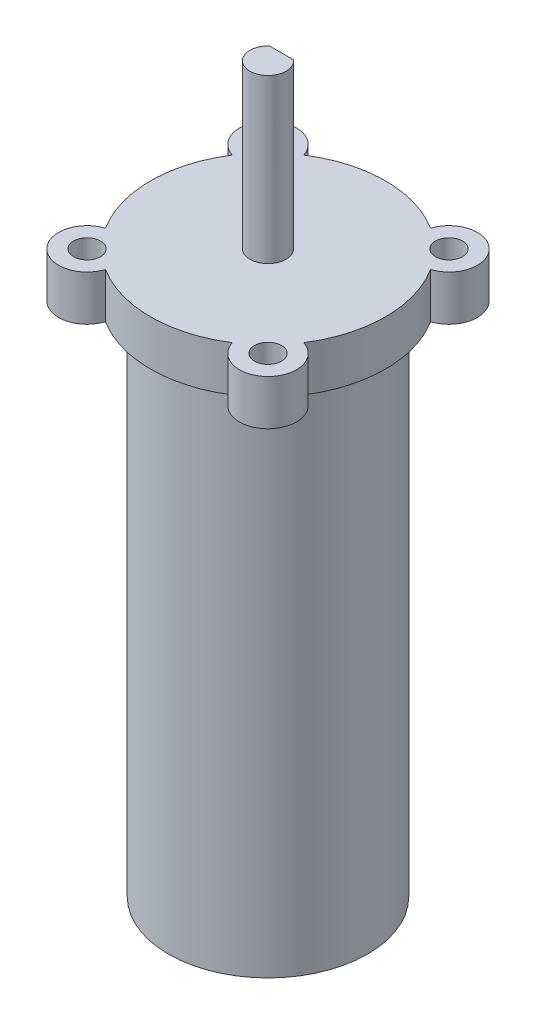
SolidWorks part; units mm, degrees
ref_plane "前视基准面" through (0, 0, 0) normal (0, 0, 1) x (1, 0, 0)
ref_plane "上视基准面" through (0, 0, 0) normal (0, 1, 0) x (1, 0, 0)
ref_plane "右视基准面" through (0, 0, 0) normal (1, 0, 0) x (0, 0, -1)
sketch "Sketch1" plane through (0, 0, 0) normal (0, 1, 0) x (1, 0, 0)
  circle A0 centre (0, 0) radius 11
extrude "Extrude1" add sketch "Sketch1" along normal blind 62
sketch "Sketch2" plane through (0, 62, 0) normal (0, 1, 0) x (1, 0, 0)
  circle A0 centre (0, 0) radius 2
extrude "Extrude2" add sketch "Sketch2" along normal blind 18
sketch "Sketch3" plane through (0, 0, 0) normal (0, -1, 0) x (1, 0, 0)
  circle A0 centre (10, -10) radius 1.5
  circle A1 centre (10, 10) radius 1.5
  circle A2 centre (-10, 10) radius 1.5
  circle A3 centre (-10, -10) radius 1.5
  circle A4 centre (0, 0) radius 11 construction
  circle A5 centre (0, 0) radius 11
  arc A6 (10.9511, -7.0053) -> (10.9511, 7.0053) centre (0, 0) ccw
  arc A7 (7.0053, -10.9511) -> (10.9511, -7.0053) centre (10, -10) ccw
  arc A8 (10.9511, 7.0053) -> (7.0053, 10.9511) centre (10, 10) ccw
  arc A9 (-7.0053, 10.9511) -> (-10.9511, 7.0053) centre (-10, 10) ccw
  arc A10 (-10.9511, -7.0053) -> (-7.0053, -10.9511) centre (-10, -10) ccw
  circle A11 centre (0, 0) radius 13 construction
  arc A12 (7.0053, 10.9511) -> (-7.0053, 10.9511) centre (0, 0) ccw
  arc A13 (-10.9511, 7.0053) -> (-10.9511, -7.0053) centre (0, 0) ccw
  arc A14 (-7.0053, -10.9511) -> (7.0053, -10.9511) centre (0, 0) ccw
  dimension "D1" = 2
extrude "Extrude3" add sketch "Sketch3" against normal up to surface (62 mm away) up to face at (0, 62, 2)
sketch "Sketch4" plane through (0, 0, 0) normal (0, -1, 0) x (1, 0, 0)
  circle A0 centre (0, 0) radius 11
  circle A1 centre (0, 0) radius 20.9212
extrude "Extrude4" cut sketch "Sketch4" against normal offset from surface (57 mm away) 5 up to face at (0, 62, 2)
sketch "Sketch5" plane through (0, 80, 0) normal (0, 1, 0) x (1, 0, 0)
  line L1 (-1.3229, 1.5) -> (1.3229, 1.5)
  circle A0 centre (0, 0) radius 2 construction
  arc A1 (1.3229, 1.5) -> (-1.3229, 1.5) centre (0, 0) ccw
  point P9 (0, 1.5)
extrude "Extrude5" cut sketch "Sketch5" against normal blind 12
